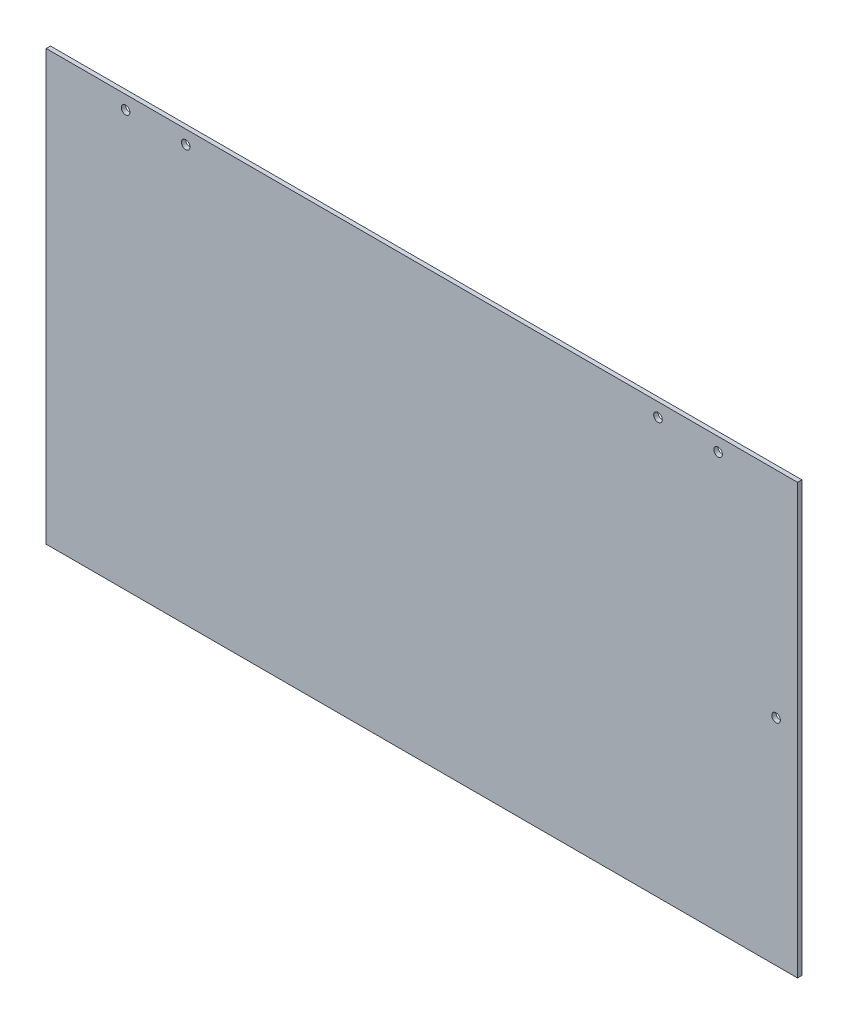
SolidWorks part; units mm, degrees
ref_plane "前视基准面" through (0, 0, 0) normal (0, 0, 1) x (1, 0, 0)
ref_plane "上视基准面" through (0, 0, 0) normal (0, 1, 0) x (1, 0, 0)
ref_plane "右视基准面" through (0, 0, 0) normal (1, 0, 0) x (0, 0, -1)
sketch "草图1" plane through (0, 0, 0) normal (0, 0, 1) x (1, 0, 0)
  line L0 (0, 0) -> (0, 4) construction
  line L1 (0, 0) -> (350, 0)
  line L2 (0, 0) -> (0, -200)
  line L3 (0, -200) -> (350, -200)
  line L4 (350, 0) -> (350, -200)
  line L5 (0, 4) -> (2, 4) construction
  line L6 (2, 4) -> (2, 0) construction
  line L8 (0, -200) -> (0, -204) construction
  line L9 (0, -204) -> (2, -204) construction
  line L10 (2, -204) -> (2, -200) construction
  line L12 (175, 0) -> (175, -200) construction
  line L13 (285, -6.3) -> (313, -6.3) construction
  circle A0 centre (340, -100) radius 2
  circle A1 centre (285, -6.3) radius 2
  circle A2 centre (313, -6.3) radius 2
  circle A3 centre (37, -6.3) radius 2
  circle A4 centre (65, -6.3) radius 2
  dimension "D4" = 10
  dimension "D5" = 4
  dimension "D6" = 4
  dimension "D1" = 200
  dimension "D2" = 350
  dimension "D3" = 4
  dimension "D7" = 28
  dimension "D8" = 6.3
  dimension "D9" = 220
extrude "凸台-拉伸1" add sketch "草图1" along normal blind 2
